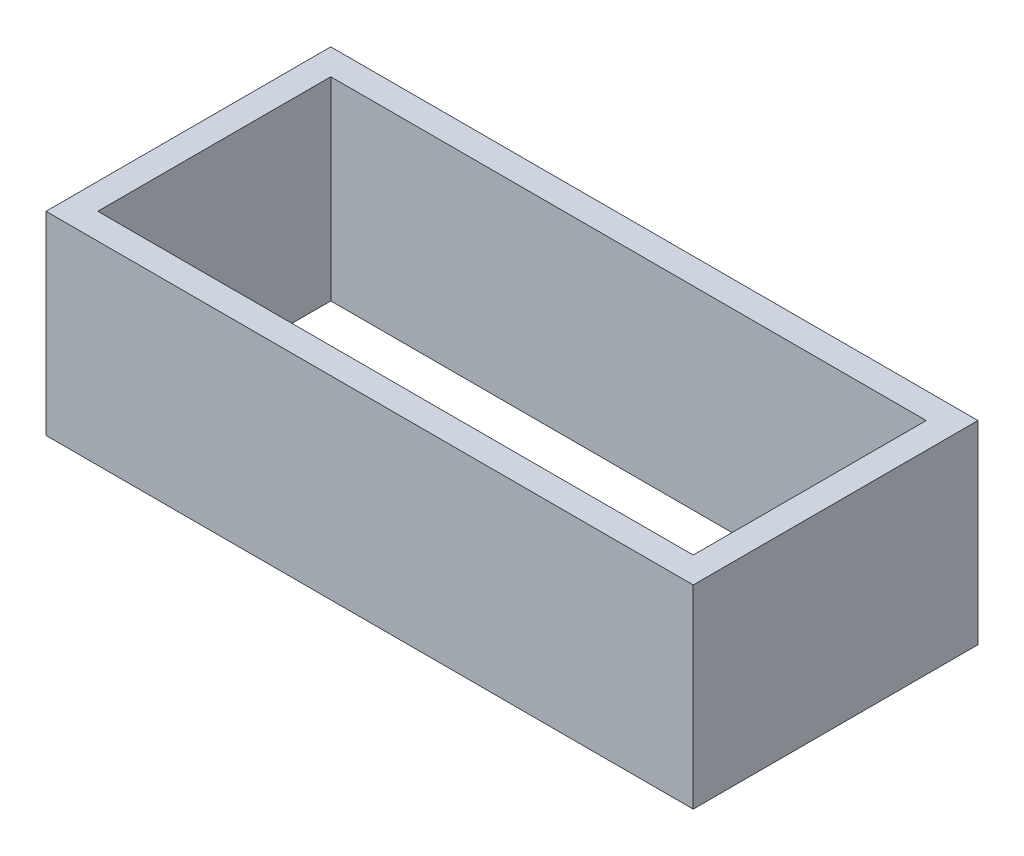
SolidWorks part; units mm, degrees
ref_plane "Front Plane" through (0, 0, 0) normal (0, 0, 1) x (1, 0, 0)
ref_plane "Top Plane" through (0, 0, 0) normal (0, 1, 0) x (1, 0, 0)
ref_plane "Right Plane" through (0, 0, 0) normal (1, 0, 0) x (0, 0, -1)
sketch "Sketch2" plane through (0, 0, 0) normal (0, 1, 0) x (1, 0, 0)
  line L5 (-50, -22) -> (50, -22)
  line L6 (-50, -22) -> (-50, 22)
  line L11 (-50, 22) -> (50, 22)
  line L12 (50, -22) -> (50, 22)
  line L13 (-50, -22) -> (50, 22) construction
  line L14 (-50, 22) -> (50, -22) construction
  line L15 (-46, 18) -> (46, 18)
  line L16 (-46, 18) -> (-46, -18)
  line L17 (-46, -18) -> (46, -18)
  line L18 (46, 18) -> (46, -18)
  line L19 (-46, 18) -> (46, -18) construction
  line L20 (-46, -18) -> (46, 18) construction
  point P0 (0, 0)
  point P6 (0, 0)
  dimension "D1" = 100
  dimension "D2" = 44
  dimension "D3" = 4
  dimension "D4" = 4
extrude "Boss-Extrude2" add sketch "Sketch2" along normal blind 30
